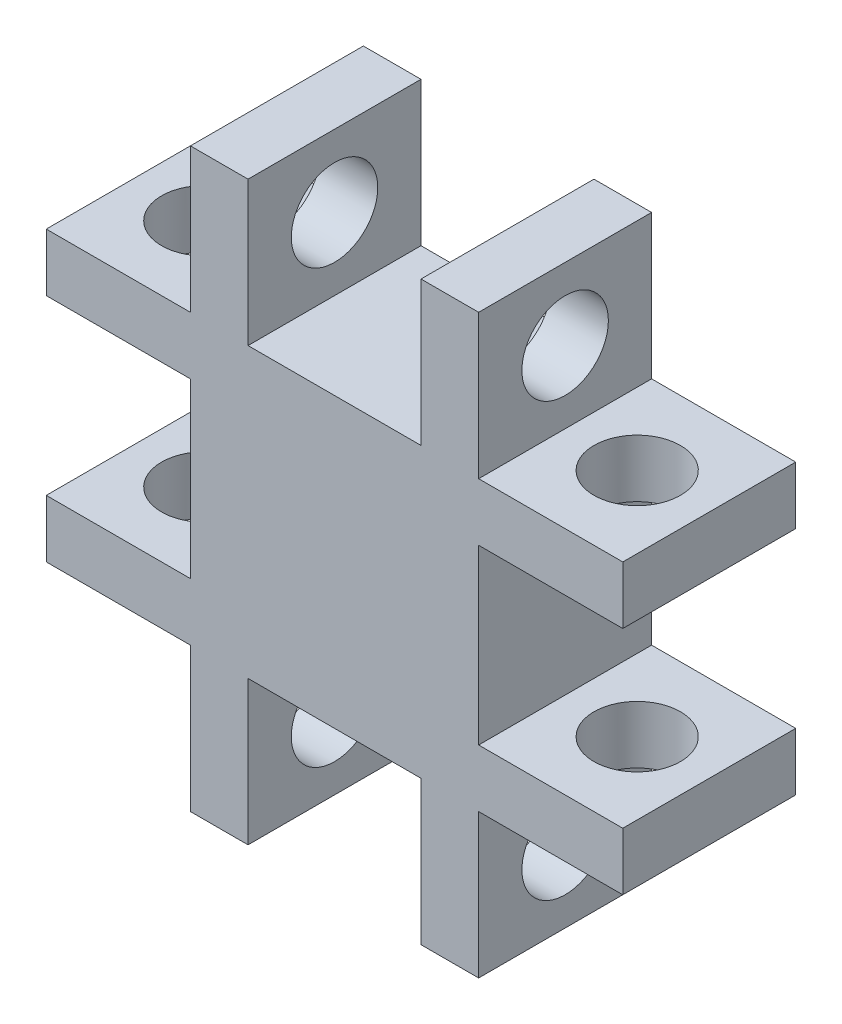
SolidWorks part; units mm, degrees
ref_plane "Front Plane" through (0, 0, 0) normal (0, 0, 1) x (1, 0, 0)
ref_plane "Top Plane" through (0, 0, 0) normal (0, 1, 0) x (1, 0, 0)
ref_plane "Right Plane" through (0, 0, 0) normal (1, 0, 0) x (0, 0, -1)
sketch "Sketch1" plane through (0, 0, 0) normal (0, 0, 1) x (1, 0, 0)
  line L1 (-50, 50) -> (50, 50)
  line L2 (-50, 50) -> (-50, -50)
  line L3 (-50, -50) -> (50, -50)
  line L4 (50, 50) -> (50, -50)
  line L5 (-50, 50) -> (50, -50) construction
  line L6 (-50, -50) -> (50, 50) construction
  point P0 (0, 0)
  dimension "D1" = 100
  dimension "D2" = 100
extrude "Boss-Extrude1" add sketch "Sketch1" along normal blind 60
ref_plane "Plane1" through (0, 0, 0) normal (1, 0, 0) x (0, 0, -1)
ref_plane "Plane2" through (0, 0, 0) normal (0, 1, 0) x (1, 0, 0)
sketch "Sketch2" plane through (50, 0, 0) normal (1, 0, 0) x (0, 0, -1)
  line L0 (0, -50) -> (0, 50) construction
  line L1 (-60, 50) -> (0, 50)
  line L2 (-60, 50) -> (-60, 30)
  line L3 (-60, 30) -> (0, 30)
  line L4 (0, 50) -> (0, 30)
  line L6 (-60, -50) -> (0, -50)
  line L7 (-60, -50) -> (-60, -30)
  line L8 (-60, -30) -> (0, -30)
  line L9 (0, -50) -> (0, -30)
  dimension "D1" = 20
  dimension "D2" = 20
extrude "Boss-Extrude2" add sketch "Sketch2" along normal blind 50
sketch "Sketch3" plane through (0, -50, 0) normal (0, -1, 0) x (1, 0, 0)
  line L0 (-50, 60) -> (100, 60) construction
  line L1 (-50, 60) -> (-30, 60)
  line L2 (-50, 60) -> (-50, 0)
  line L3 (-50, 0) -> (-30, 0)
  line L4 (-30, 60) -> (-30, 0)
  line L5 (-50, 0) -> (100, 0) construction
  line L6 (100, 60) -> (100, 0) construction
  line L7 (50, 60) -> (30, 60)
  line L8 (50, 60) -> (50, 0)
  line L9 (50, 0) -> (30, 0)
  line L10 (30, 60) -> (30, 0)
  dimension "D1" = 50
  dimension "D2" = 20
  dimension "D4" = 20
extrude "Boss-Extrude3" add sketch "Sketch3" along normal blind 50
sketch "Sketch4" plane through (0, -50, 0) normal (0, -1, 0) x (1, 0, 0)
  line L0 (50, 0) -> (50, 60) construction
  line L1 (50, 0) -> (100, 0) construction
  circle A0 centre (75, 30) radius 15
  dimension "D3" = 30
  dimension "D1" = 25
  dimension "D2" = 30
extrude "Cut-Extrude1" cut sketch "Sketch4" against normal blind 100
sketch "Sketch5" plane through (50, 0, 0) normal (1, 0, 0) x (0, 0, -1)
  line L0 (-60, -100) -> (-60, -50) construction
  line L1 (0, -50) -> (-60, -50) construction
  circle A0 centre (-30, -75) radius 15
  dimension "D3" = 30
  dimension "D1" = 30
  dimension "D2" = 25
extrude "Cut-Extrude2" cut sketch "Sketch5" against normal blind 100
mirror "Mirror2" about plane through (0, 0, 0) normal (1, 0, 0) of "Cut-Extrude1", "Boss-Extrude2"
mirror "Mirror3" about plane through (0, 0, 0) normal (0, 1, 0) of "Cut-Extrude2", "Boss-Extrude3"
